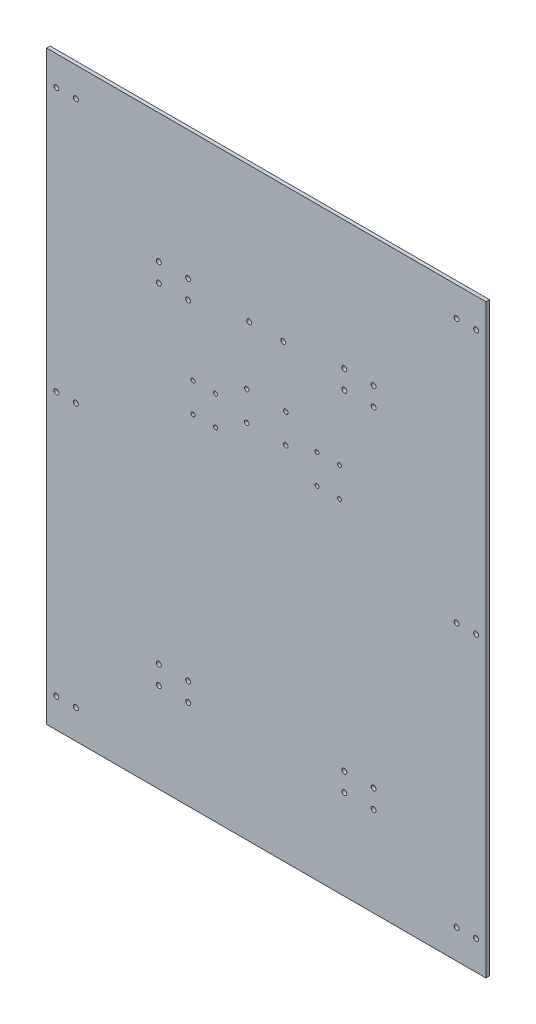
SolidWorks part; units mm, degrees
material "处理板，复杂型"
ref_plane "前视基准面" through (0, 0, 0) normal (0, 0, 1) x (1, 0, 0)
ref_plane "上视基准面" through (0, 0, 0) normal (0, 1, 0) x (1, 0, 0)
ref_plane "右视基准面" through (0, 0, 0) normal (1, 0, 0) x (0, 0, -1)
sketch "草图1" plane through (0, 0, 0) normal (0, 0, 1) x (1, 0, 0)
  line L0 (0, 25.8706) -> (0, -31.2111) construction
  line L1 (-225, 300) -> (225, 300)
  line L2 (-225, 300) -> (-225, -300)
  line L3 (-225, -300) -> (225, -300)
  line L4 (225, 300) -> (225, -300)
  line L5 (-23.9883, 0) -> (45.7004, 0) construction
  dimension "D1" = 450
  dimension "D2" = 600
  dimension "D3" = 225
  dimension "D4" = 300
extrude "凸台-拉伸1" add sketch "草图1" along normal blind 3.6
sketch "草图4" plane through (0, 0, 3.6) normal (0, 0, 1) x (1, 0, 0)
  line L0 (0, 355.7202) -> (0, -488.737) construction
  line L1 (-385.3696, 0) -> (469.6692, 0) construction
  line L2 (-195, 355.7202) -> (-195, -398.416) construction
  line L3 (195, -398.416) -> (195, 398.416) construction
  line L4 (-371.3197, 270) -> (369.3125, 270) construction
  line L5 (-343.2198, -270) -> (413.4695, -270) construction
  line L6 (225, -300) -> (225, 300) construction
  line L7 (225, 300) -> (-225, 300) construction
  line L8 (-225, 300) -> (-225, -300) construction
  line L9 (-225, -300) -> (225, -300) construction
  line L10 (-205, -325.8576) -> (-205, 461.6631) construction
  line L11 (205, -325.8576) -> (205, 461.6631) construction
  circle A0 centre (-195, 270) radius 2.5
  circle A1 centre (-195, -270) radius 2.5
  circle A2 centre (195, -270) radius 2.5
  circle A3 centre (195, 270) radius 2.5
  circle A4 centre (-195, 0) radius 2.5
  circle A5 centre (195, 0) radius 2.5
  circle A7 centre (-215, -270) radius 2.5
  circle A8 centre (-215, 0) radius 2.5
  circle A9 centre (-215, 270) radius 2.5
  circle A10 centre (215, 270) radius 2.5
  circle A11 centre (215, 0) radius 2.5
  circle A12 centre (215, -270) radius 2.5
  dimension "D5" = 5
  dimension "D6" = 5
  dimension "D7" = 5
  dimension "D8" = 5
  dimension "D9" = 5
  dimension "D10" = 5
  dimension "D1" = 30
  dimension "D2" = 30
  dimension "D3" = 30
  dimension "D4" = 30
  dimension "D11" = 10
extrude "切除-拉伸3" cut sketch "草图4" against normal blind 3.6
sketch "草图5" plane through (0, 0, 3.6) normal (0, 0, 1) x (1, 0, 0)
  circle A0 centre (-75, 50) radius 2
  circle A1 centre (-75, 80) radius 2
  circle A2 centre (-52, 50) radius 2
  circle A3 centre (-52, 80) radius 2
extrude "切除-拉伸4" cut sketch "草图5" against normal blind 10
sketch "草图6" plane through (0, 0, 3.6) normal (0, 0, 1) x (1, 0, 0)
  circle A0 centre (52, 50) radius 2
  circle A1 centre (52, 80) radius 2
  circle A2 centre (75, 50) radius 2
  circle A3 centre (75, 80) radius 2
extrude "切除-拉伸5" cut sketch "草图6" against normal blind 10
sketch "草图7" plane through (0, 0, 3.6) normal (0, 0, 1) x (1, 0, 0)
  circle A0 centre (-17.5, 161) radius 2.5
  circle A1 centre (17.5, 161) radius 2.5
extrude "切除-拉伸6" cut sketch "草图7" against normal blind 10
sketch "草图8" plane through (0, 0, 3.6) normal (0, 0, 1) x (1, 0, 0)
  circle A0 centre (-20, 70) radius 2.25
  circle A1 centre (-20, 100) radius 2.25
  circle A2 centre (20, 70) radius 2.25
  circle A3 centre (20, 100) radius 2.25
extrude "切除-拉伸7" cut sketch "草图8" against normal through all
sketch "草图9" plane through (0, 0, 3.6) normal (0, 0, 1) x (1, 0, 0)
  circle A0 centre (-110, -208) radius 2.5
  circle A1 centre (-110, -189) radius 2.5
  circle A2 centre (-80, -208) radius 2.5
  circle A3 centre (-80, -189) radius 2.5
  circle A4 centre (80, -208) radius 2.5
  circle A5 centre (80, -189) radius 2.5
  circle A6 centre (110, -189) radius 2.5
  circle A7 centre (110, -208) radius 2.5
  circle A8 centre (110, 149) radius 2.5
  circle A9 centre (110, 168) radius 2.5
  circle A10 centre (80, 149) radius 2.5
  circle A11 centre (80, 168) radius 2.5
  circle A12 centre (-80, 149) radius 2.5
  circle A13 centre (-80, 168) radius 2.5
  circle A14 centre (-110, 149) radius 2.5
  circle A15 centre (-110, 168) radius 2.5
extrude "切除-拉伸8" cut sketch "草图9" against normal through all
